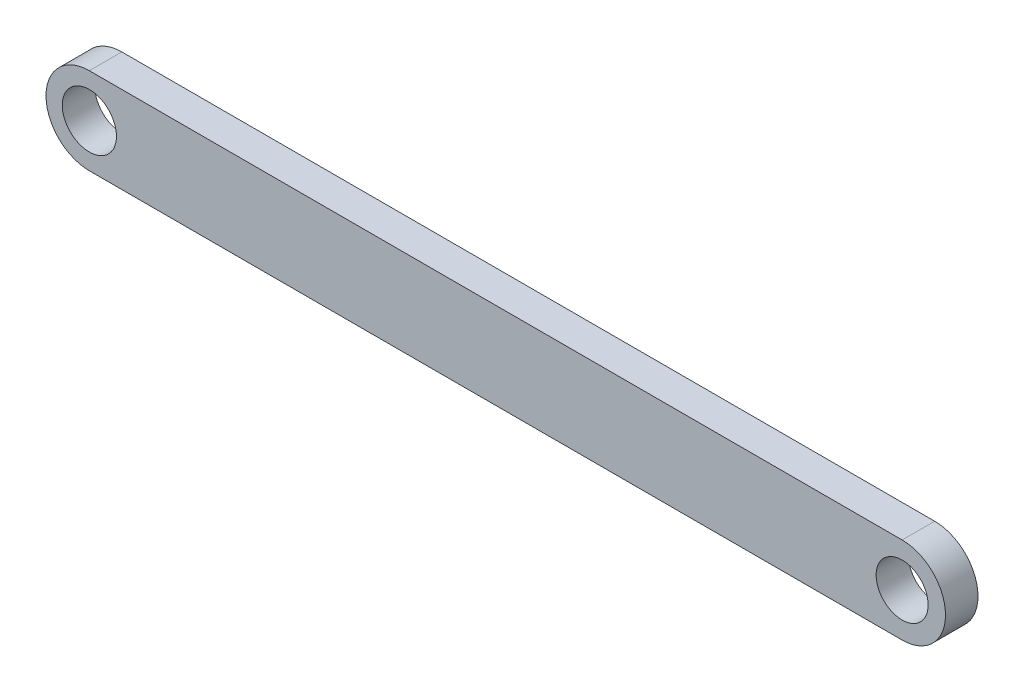
SolidWorks part; units mm, degrees
ref_plane "Front Plane" through (0, 0, 0) normal (0, 0, 1) x (1, 0, 0)
ref_plane "Top Plane" through (0, 0, 0) normal (0, 1, 0) x (1, 0, 0)
ref_plane "Right Plane" through (0, 0, 0) normal (1, 0, 0) x (0, 0, -1)
sketch "Sketch1" plane through (0, 34.7031, 0) normal (0, 0, 1) x (1, 0, 0)
  line L1 (-30.3724, 17.4326) -> (44.6276, 17.4326)
  line L3 (-30.3724, 9.4326) -> (44.6276, 9.4326)
  arc A0 (-30.3724, 17.4326) -> (-30.3724, 9.4326) centre (-30.3724, 13.4326) ccw
  arc A1 (44.6276, 17.4326) -> (44.6276, 9.4326) centre (44.6276, 13.4326) cw
  circle A2 centre (-30.3724, 13.4326) radius 2.5
  circle A3 centre (44.6276, 13.4326) radius 2.4
  dimension "D3" = 5
  dimension "D4" = 4.8
  dimension "D1" = 75
  dimension "D2" = 8
extrude "Boss-Extrude1" add sketch "Sketch1" along normal blind 3
